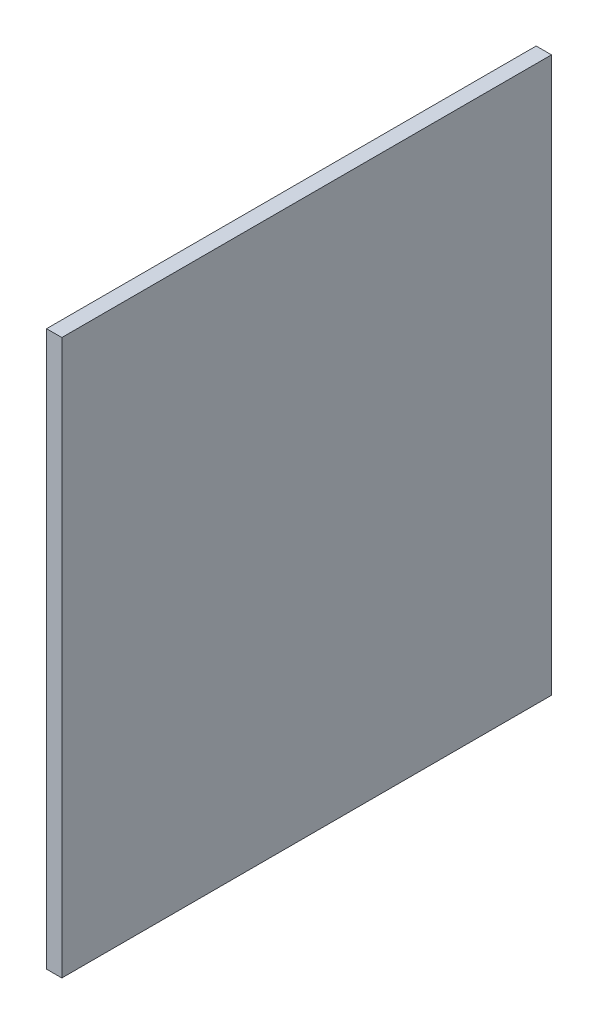
SolidWorks part; units mm, degrees
ref_plane "Front Plane" through (0, 0, 0) normal (0, 0, 1) x (1, 0, 0)
ref_plane "Top Plane" through (0, 0, 0) normal (0, 1, 0) x (1, 0, 0)
ref_plane "Right Plane" through (0, 0, 0) normal (1, 0, 0) x (0, 0, -1)
sketch "Sketch1" plane through (0, 0, 0) normal (1, 0, 0) x (0, 0, -1)
  line L1 (-756.5217, 508.8509) -> (523.4783, 508.8509)
  line L2 (-756.5217, 508.8509) -> (-756.5217, -941.1491)
  line L3 (-756.5217, -941.1491) -> (523.4783, -941.1491)
  line L4 (523.4783, 508.8509) -> (523.4783, -941.1491)
  dimension "D1" = 1450
  dimension "D2" = 1280
extrude "Boss-Extrude1" add sketch "Sketch1" along normal blind 40
